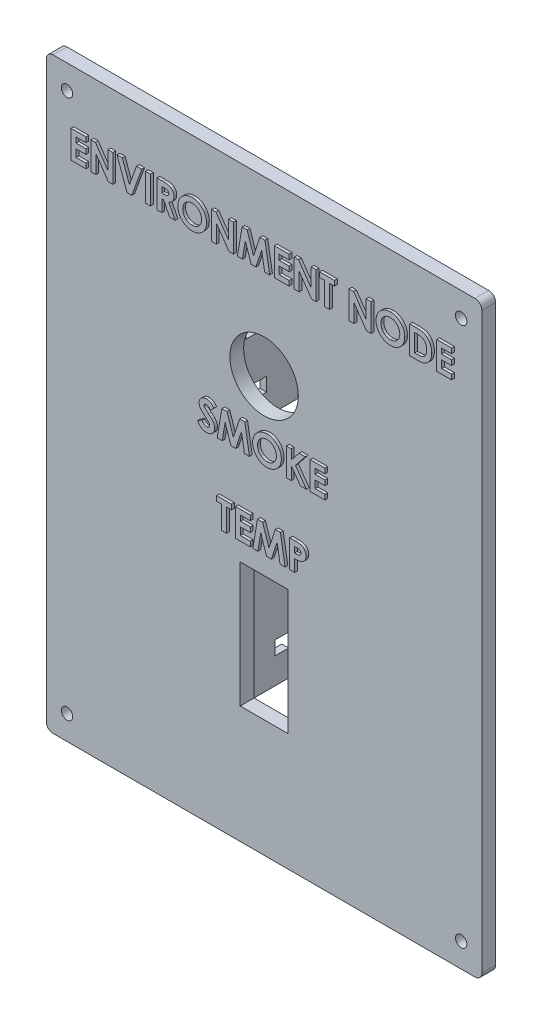
SolidWorks part; units mm, degrees
ref_plane "Front Plane" through (0, 0, 0) normal (0, 0, 1) x (1, 0, 0)
ref_plane "Top Plane" through (0, 0, 0) normal (0, 1, 0) x (1, 0, 0)
ref_plane "Right Plane" through (0, 0, 0) normal (1, 0, 0) x (0, 0, -1)
sketch "Sketch1" plane through (0, 0, 0) normal (0, 0, 1) x (1, 0, 0)
  line L0 (-61, 0) -> (61, 0)
  line L1 (63, 2) -> (63, 168)
  line L2 (61, 170) -> (-61, 170)
  line L3 (-63, 168) -> (-63, 2)
  arc A0 (-63, 2) -> (-61, 0) centre (-61, 2) ccw
  arc A1 (61, 0) -> (63, 2) centre (61, 2) ccw
  arc A2 (63, 168) -> (61, 170) centre (61, 168) ccw
  arc A3 (-61, 170) -> (-63, 168) centre (-61, 168) ccw
extrude "Panel" add sketch "Sketch1" along normal blind 4
ref_plane "P1_Front_4" through (0, 0, 4) normal (0, 0, 1) x (1, 0, 0)
sketch "Sketch2" plane through (0, 0, 0) normal (0, 0, 1) x (1, 0, 0)
  circle A0 centre (-57, 7) radius 1.65
  circle A1 centre (57, 7) radius 1.65
  circle A2 centre (-57, 163) radius 1.65
  circle A3 centre (57, 163) radius 1.65
extrude "Screw holes" cut sketch "Sketch2" along normal through all
ref_plane "P2_Front_-3" through (0, 0, -3) normal (0, 0, 1) x (1, 0, 0)
sketch "Sketch3" plane through (0, 0, -3) normal (0, 0, 1) x (1, 0, 0)
  line L1 (-15, 3.3) -> (15, 3.3)
  line L2 (-15, 3.3) -> (-15, 5.3)
  line L3 (-15, 5.3) -> (15, 5.3)
  line L4 (15, 3.3) -> (15, 5.3)
  line L6 (-15, 164.7) -> (15, 164.7)
  line L7 (-15, 164.7) -> (-15, 166.7)
  line L8 (-15, 166.7) -> (15, 166.7)
  line L9 (15, 164.7) -> (15, 166.7)
  line L11 (-58.4574, 70) -> (-56.4574, 70)
  line L12 (-58.4574, 70) -> (-58.4574, 100)
  line L13 (-58.4574, 100) -> (-56.4574, 100)
  line L14 (-56.4574, 70) -> (-56.4574, 100)
  line L16 (56.4574, 70) -> (58.4574, 70)
  line L17 (56.4574, 70) -> (56.4574, 100)
  line L18 (56.4574, 100) -> (58.4574, 100)
  line L19 (58.4574, 70) -> (58.4574, 100)
extrude "Locating tabs" add sketch "Sketch3" along normal blind 3
sketch "Sketch4" plane through (0, 0, 0) normal (0, 0, 1) x (1, 0, 0)
  circle A0 centre (0, 120) radius 9.905
extrude "MQ-2 can hole" cut sketch "Sketch4" along normal through all
ref_plane "P3_Front_-16" through (0, 0, -16) normal (0, 0, 1) x (1, 0, 0)
sketch "Sketch5" plane through (0, 0, -16) normal (0, 0, 1) x (1, 0, 0)
  line L1 (-12.25, 99.28) -> (-10.25, 99.28)
  line L2 (-12.25, 99.28) -> (-12.25, 131.8)
  line L3 (-12.25, 131.8) -> (-10.25, 131.8)
  line L4 (-10.25, 99.28) -> (-10.25, 131.8)
  line L6 (10.25, 99.28) -> (12.25, 99.28)
  line L7 (10.25, 99.28) -> (10.25, 131.8)
  line L8 (10.25, 131.8) -> (12.25, 131.8)
  line L9 (12.25, 99.28) -> (12.25, 131.8)
extrude "MQ-2 rails" add sketch "Sketch5" along normal blind 16
ref_plane "P4_Right_-13.25" through (-13.25, 0, 0) normal (1, 0, 0) x (0, 0, -1)
sketch "Sketch6" plane through (-13.25, 0, 0) normal (1, 0, 0) x (0, 0, -1)
  line L1 (1, 105.41) -> (7, 105.41)
  line L2 (1, 105.41) -> (1, 109.41)
  line L3 (1, 109.41) -> (7, 109.41)
  line L4 (7, 105.41) -> (7, 109.41)
  line L5 (1, 105.41) -> (7, 109.41) construction
  line L6 (1, 109.41) -> (7, 105.41) construction
  line L7 (1, 121.67) -> (7, 121.67)
  line L8 (1, 121.67) -> (1, 125.67)
  line L9 (1, 125.67) -> (7, 125.67)
  line L10 (7, 121.67) -> (7, 125.67)
  line L11 (1, 121.67) -> (7, 125.67) construction
  line L12 (1, 125.67) -> (7, 121.67) construction
  point P0 (4, 107.41)
  point P5 (4, 123.67)
extrude "MQ-2 tie slots" cut sketch "Sketch6" along normal through all
sketch "Sketch7" plane through (0, 0, 0) normal (0, 0, 1) x (1, 0, 0)
  line L1 (-6.9, 33.95) -> (6.9, 33.95)
  line L2 (-6.9, 33.95) -> (-6.9, 70.05)
  line L3 (-6.9, 70.05) -> (6.9, 70.05)
  line L4 (6.9, 33.95) -> (6.9, 70.05)
  line L5 (-6.9, 33.95) -> (6.9, 70.05) construction
  line L6 (-6.9, 70.05) -> (6.9, 33.95) construction
  point P0 (0, 52)
extrude "DHT22 window" cut sketch "Sketch7" along normal through all
ref_plane "P5_Front_-11" through (0, 0, -11) normal (0, 0, 1) x (1, 0, 0)
sketch "Sketch8" plane through (0, 0, -11) normal (0, 0, 1) x (1, 0, 0)
  line L1 (-9.9, 32.95) -> (-7.9, 32.95)
  line L2 (-9.9, 32.95) -> (-9.9, 71.05)
  line L3 (-9.9, 71.05) -> (-7.9, 71.05)
  line L4 (-7.9, 32.95) -> (-7.9, 71.05)
  line L6 (7.9, 32.95) -> (9.9, 32.95)
  line L7 (7.9, 32.95) -> (7.9, 71.05)
  line L8 (7.9, 71.05) -> (9.9, 71.05)
  line L9 (9.9, 32.95) -> (9.9, 71.05)
extrude "DHT22 rails" add sketch "Sketch8" along normal blind 11
ref_plane "P6_Right_-10.9" through (-10.9, 0, 0) normal (1, 0, 0) x (0, 0, -1)
sketch "Sketch9" plane through (-10.9, 0, 0) normal (1, 0, 0) x (0, 0, -1)
  line L1 (7, 40.475) -> (11, 40.475)
  line L2 (7, 40.475) -> (7, 44.475)
  line L3 (7, 44.475) -> (11, 44.475)
  line L4 (11, 40.475) -> (11, 44.475)
  line L5 (7, 40.475) -> (11, 44.475) construction
  line L6 (7, 44.475) -> (11, 40.475) construction
  line L7 (7, 59.525) -> (11, 59.525)
  line L8 (7, 59.525) -> (7, 63.525)
  line L9 (7, 63.525) -> (11, 63.525)
  line L10 (11, 59.525) -> (11, 63.525)
  line L11 (7, 59.525) -> (11, 63.525) construction
  line L12 (7, 63.525) -> (11, 59.525) construction
  point P0 (9, 42.475)
  point P5 (9, 61.525)
extrude "DHT22 tie slots" cut sketch "Sketch9" along normal through all
ref_plane "P7_Front_-11" through (0, 0, -11) normal (0, 0, 1) x (1, 0, 0)
sketch "Sketch10" plane through (0, 0, -11) normal (0, 0, 1) x (1, 0, 0)
  line L1 (-9.9, 71.05) -> (9.9, 71.05)
  line L2 (-9.9, 71.05) -> (-9.9, 73.05)
  line L3 (-9.9, 73.05) -> (9.9, 73.05)
  line L4 (9.9, 71.05) -> (9.9, 73.05)
extrude "DHT22 pocket top" add sketch "Sketch10" along normal blind 11
sketch "Sketch11" plane through (0, 0, 4) normal (0, 0, 1) x (1, 0, 0)
  text T0 "ENVIRONMENT NODE" font "Century Gothic" height 8
  text T1 "SMOKE" font "Century Gothic" height 8
  text T2 "TEMP" font "Century Gothic" height 8
extrude "Labels (raised)" add sketch "Sketch11" along normal blind 0.8
